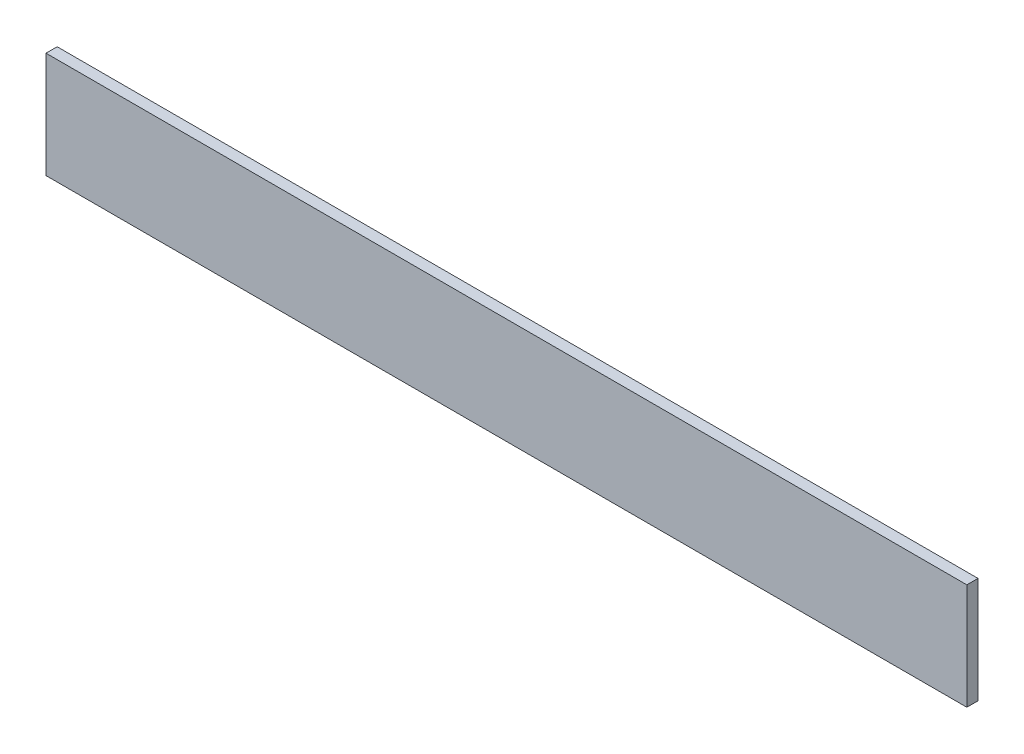
SolidWorks part; units mm, degrees
ref_plane "前视基准面" through (0, 0, 0) normal (0, 0, 1) x (1, 0, 0)
ref_plane "上视基准面" through (0, 0, 0) normal (0, 1, 0) x (1, 0, 0)
ref_plane "右视基准面" through (0, 0, 0) normal (1, 0, 0) x (0, 0, -1)
sketch "草图1" plane through (0, 0, 0) normal (0, 0, 1) x (1, 0, 0)
  line L1 (0, 0) -> (660, 0)
  line L2 (0, 0) -> (0, -76)
  line L3 (0, -76) -> (660, -76)
  line L4 (660, 0) -> (660, -76)
extrude "凸台-拉伸1" add sketch "草图1" along normal blind 8
